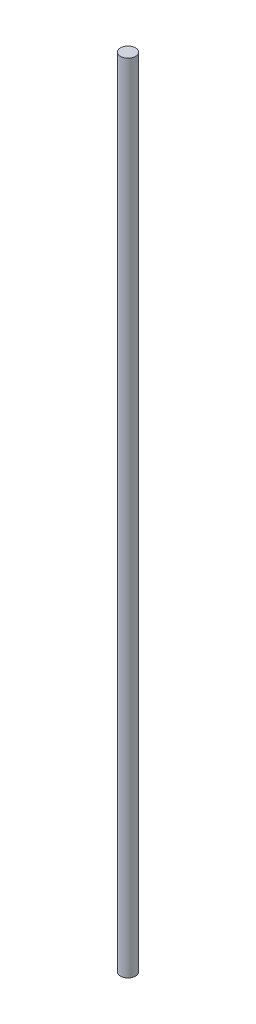
SolidWorks part; units mm, degrees
material "Thornel Mat VMA"
ref_plane "前视基准面" through (0, 0, 0) normal (0, 0, 1) x (1, 0, 0)
ref_plane "上视基准面" through (0, 0, 0) normal (0, 1, 0) x (1, 0, 0)
ref_plane "右视基准面" through (0, 0, 0) normal (1, 0, 0) x (0, 0, -1)
sketch "草图1" plane through (0, 0, 0) normal (0, 1, 0) x (1, 0, 0)
  circle A0 centre (0, 0) radius 0.75
  dimension "D1" = 1.5
extrude "凸台-拉伸1" add sketch "草图1" along normal blind 80
equation "\"m\"= 2"
